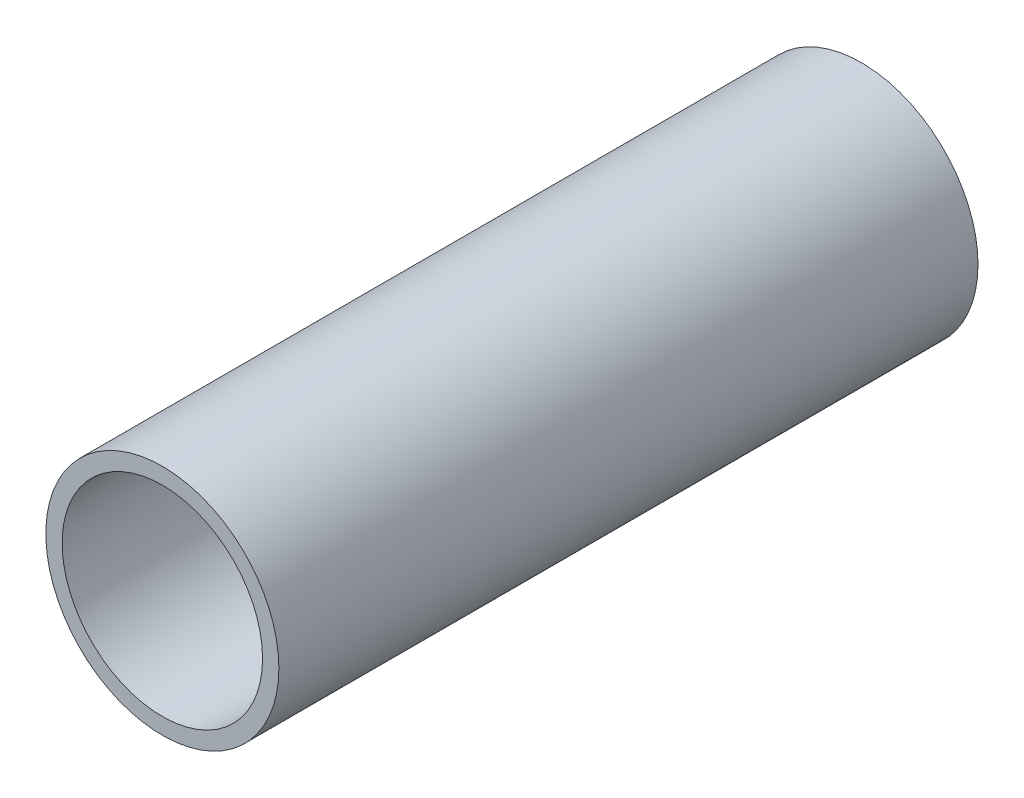
SolidWorks part; units mm, degrees
ref_plane "Front" through (0, 0, 0) normal (0, 0, 1) x (1, 0, 0)
ref_plane "Top" through (0, 0, 0) normal (0, 1, 0) x (1, 0, 0)
ref_plane "Right" through (0, 0, 0) normal (1, 0, 0) x (0, 0, -1)
sketch "Sketch1" plane through (0, 0, 0) normal (0, 0, 1) x (1, 0, 0)
  circle A0 centre (0, 0) radius 6.35
  circle A1 centre (0, 0) radius 5.461
extrude "Extrude1" add sketch "Sketch1" along normal blind 38.1 contours A0 A1
sketch "Sketch2" plane through (0, 0, 0) normal (0, 1, 0) x (1, 0, 0)
  line L0 (0, 0) -> (0, -9.525)
  line L1 (0, -38.1) -> (0, -28.575)
  line L2 (-6.35, -38.1) -> (6.35, -38.1) construction
  circle A0 centre (0, -9.525) radius 2
  circle A1 centre (0, -28.575) radius 2
extrude "Cut-Extrude1" cut sketch "Sketch2" against normal blind 10 contours A0 | A1
